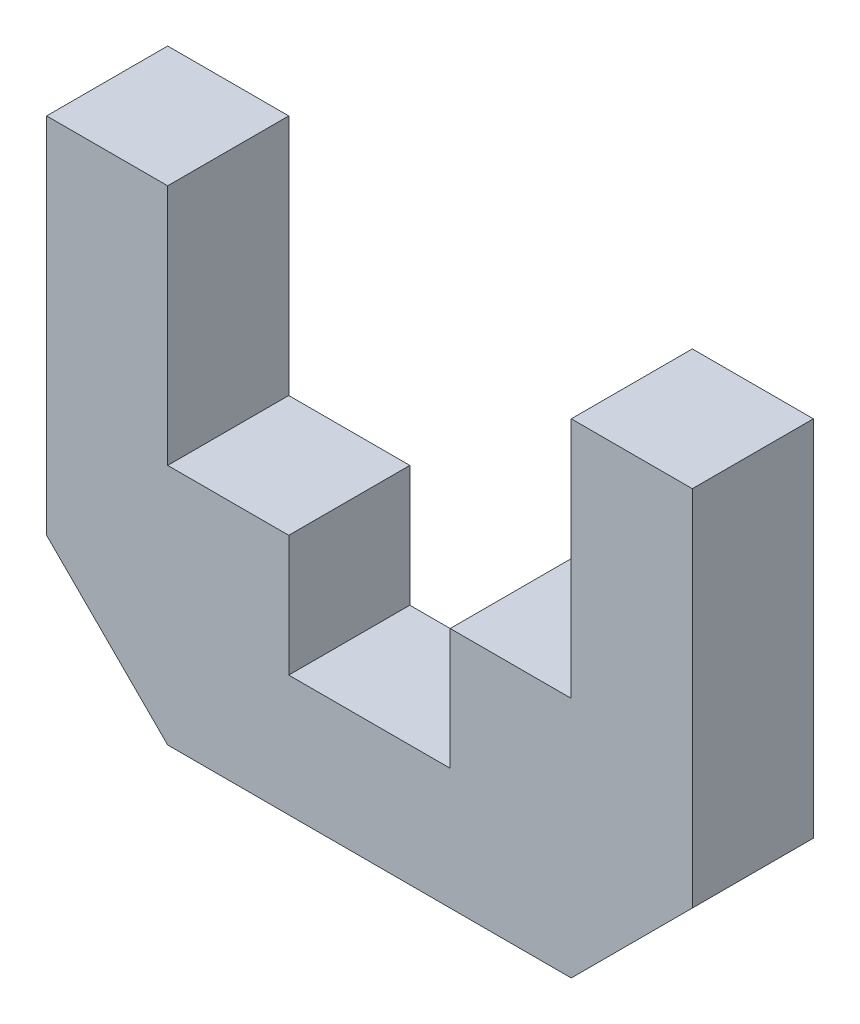
SolidWorks part; units mm, degrees
ref_plane "前视基准面" through (0, 0, 0) normal (0, 0, 1) x (1, 0, 0)
ref_plane "上视基准面" through (0, 0, 0) normal (0, 1, 0) x (1, 0, 0)
ref_plane "右视基准面" through (0, 0, 0) normal (1, 0, 0) x (0, 0, -1)
sketch "草图1" plane through (0, 0, 0) normal (0, 0, 1) x (1, 0, 0)
  line L0 (2, 0) -> (-2, 0)
  line L1 (-2, 0) -> (-2, 3)
  line L2 (-2, 3) -> (-5, 3)
  line L3 (-5, 3) -> (-5, 9)
  line L4 (-5, 9) -> (-8, 9)
  line L5 (-8, 9) -> (-8, 0)
  line L6 (0, 0) -> (0, -3) construction
  line L7 (5, -3) -> (-5, -3)
  line L8 (-5, -3) -> (-8, 0)
  line L9 (5, -3) -> (8, 0)
  line L10 (8, 9) -> (8, 0)
  line L11 (5, 9) -> (8, 9)
  line L12 (5, 3) -> (5, 9)
  line L13 (2, 3) -> (5, 3)
  line L14 (2, 0) -> (2, 3)
  point P4 (0, 0)
  dimension "D4" = 3
  dimension "D1" = 3
  dimension "D2" = 3
  dimension "D3" = 6
  dimension "D5" = 9
  dimension "D6" = 3
extrude "凸台-拉伸1" add sketch "草图1" along normal blind 3
